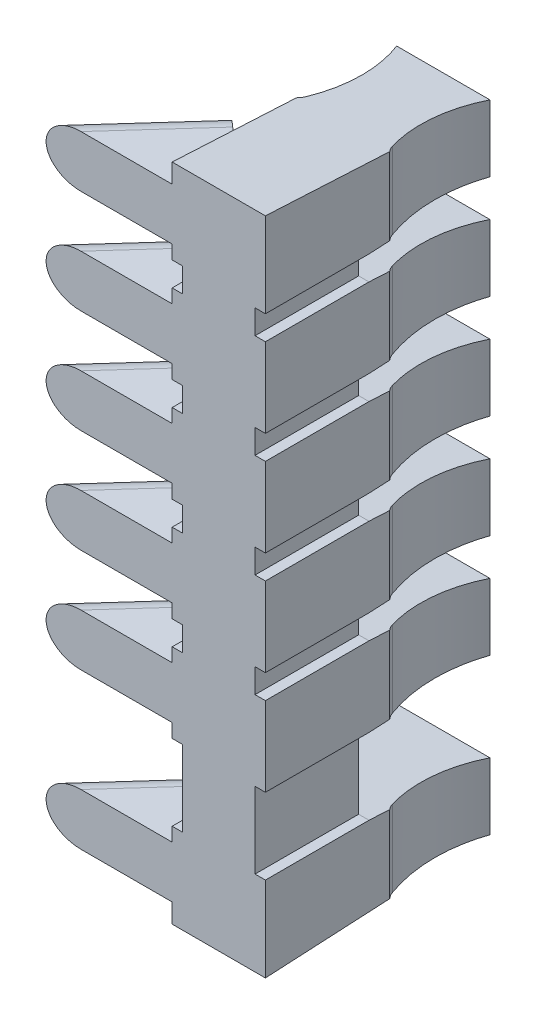
SolidWorks part; units mm, degrees
ref_plane "Front Plane" through (0, 0, 0) normal (0, 0, 1) x (1, 0, 0)
ref_plane "Top Plane" through (0, 0, 0) normal (0, 1, 0) x (1, 0, 0)
ref_plane "Right Plane" through (0, 0, 0) normal (1, 0, 0) x (0, 0, -1)
sketch "Sketch1" plane through (0, 0, 0) normal (0, 0, 1) x (1, 0, 0)
  line L0 (-7.5, 0) -> (0, 0) construction
  line L1 (-7.5, 15) -> (7.5, 15)
  line L2 (-7.5, 15) -> (-7.5, -15)
  line L3 (-7.5, -15) -> (7.5, -15)
  line L4 (7.5, 15) -> (7.5, -15)
  line L5 (0, 0) -> (0, 15) construction
  dimension "D1" = 15
  dimension "D2" = 30
sketch "Sketch2" plane through (0, 0, 0) normal (1, 0, 0) x (0, 0, -1)
  line L1 (0, 15) -> (7, 15)
  line L2 (0, 15) -> (0, -15)
  line L3 (0, -15) -> (7, -15)
  line L4 (7, 15) -> (7, -15)
  dimension "D1" = 7
extrude "Boss-Extrude1" add sketch "Sketch1" against normal up to vertex (7 mm away) up to point (0, 15, -7)
ref_plane "Plane1" through (1.35, 0, 0) normal (1, 0, 0) x (0, 0, -1)
sketch "Sketch7" plane through (1.35, 0, 0) normal (1, 0, 0) x (0, 0, -1)
  line L0 (3, 4.1005) -> (0, 4.1005) construction
  line L1 (0, 4.1005) -> (0, 6.3995) construction
  line L2 (3, 6.3995) -> (0, 6.3995) construction
  line L3 (3, 6.3995) -> (6.5, 6.2161) construction
  line L4 (6.5, 6.2161) -> (6.5, 4.2839) construction
  line L5 (6.5, 4.2839) -> (3, 4.1005) construction
  line L6 (3, 1.1005) -> (0, 1.1005) construction
  line L7 (0, 1.1005) -> (0, 3.3995) construction
  line L8 (3, 3.3995) -> (0, 3.3995) construction
  line L9 (6.5, 3.2161) -> (3, 3.3995) construction
  line L10 (6.5, 1.2839) -> (6.5, 3.2161) construction
  line L11 (3, 1.1005) -> (6.5, 1.2839) construction
  line L12 (3, -1.8995) -> (0, -1.8995) construction
  line L13 (0, -1.8995) -> (0, 0.3995) construction
  line L14 (3, 0.3995) -> (0, 0.3995) construction
  line L15 (3, 0.3995) -> (6.5, 0.2161) construction
  line L16 (6.5, 0.2161) -> (6.5, -1.7161) construction
  line L17 (6.5, -1.7161) -> (3, -1.8995) construction
  line L19 (3, -4.8995) -> (0, -4.8995) construction
  line L20 (0, -4.8995) -> (0, -2.6005) construction
  line L21 (3, -2.6005) -> (0, -2.6005) construction
  line L22 (6.5, -2.7839) -> (3, -2.6005) construction
  line L23 (6.5, -4.7161) -> (6.5, -2.7839) construction
  line L24 (3, -4.8995) -> (6.5, -4.7161) construction
  line L25 (3, -7.1005) -> (0, -7.1005) construction
  line L26 (0, -9.5567) -> (0, -7.1005) construction
  line L27 (6.5, -9.2161) -> (0, -9.5567) construction
  line L28 (6.5, -7.2839) -> (6.5, -9.2161) construction
  line L29 (3, -7.1005) -> (6.5, -7.2839) construction
  line L30 (3, 7.1005) -> (0, 7.1005) construction
  line L31 (0, 7.1005) -> (0, 9.5567) construction
  line L32 (6.5, 9.2161) -> (0, 9.5567) construction
  line L33 (6.5, 7.2839) -> (6.5, 9.2161) construction
  line L34 (3, 7.1005) -> (6.5, 7.2839) construction
  line L35 (3, 4.1005) -> (0, 4.1005)
  line L36 (0, 4.1005) -> (0, 6.3995)
  line L37 (3, 6.3995) -> (0, 6.3995)
  line L38 (3, 6.3995) -> (6.5, 6.2161)
  line L39 (6.5, 6.2161) -> (6.5, 4.2839)
  line L40 (6.5, 4.2839) -> (3, 4.1005)
  line L41 (3, 1.1005) -> (0, 1.1005)
  line L42 (0, 1.1005) -> (0, 3.3995)
  line L43 (3, 3.3995) -> (0, 3.3995)
  line L44 (6.5, 3.2161) -> (3, 3.3995)
  line L45 (6.5, 1.2839) -> (6.5, 3.2161)
  line L46 (3, 1.1005) -> (6.5, 1.2839)
  line L47 (3, -1.8995) -> (0, -1.8995)
  line L48 (0, -1.8995) -> (0, 0.3995)
  line L49 (3, 0.3995) -> (0, 0.3995)
  line L50 (3, 0.3995) -> (6.5, 0.2161)
  line L51 (6.5, 0.2161) -> (6.5, -1.7161)
  line L52 (6.5, -1.7161) -> (3, -1.8995)
  line L54 (3, -4.8995) -> (0, -4.8995)
  line L55 (0, -4.8995) -> (0, -2.6005)
  line L56 (3, -2.6005) -> (0, -2.6005)
  line L57 (6.5, -2.7839) -> (3, -2.6005)
  line L58 (6.5, -4.7161) -> (6.5, -2.7839)
  line L59 (3, -4.8995) -> (6.5, -4.7161)
  line L60 (3, -7.1005) -> (0, -7.1005)
  line L61 (0, -9.5567) -> (0, -7.1005)
  line L62 (6.5, -9.2161) -> (0, -9.5567)
  line L63 (6.5, -7.2839) -> (6.5, -9.2161)
  line L64 (3, -7.1005) -> (6.5, -7.2839)
  line L65 (3, 7.1005) -> (0, 7.1005)
  line L66 (0, 7.1005) -> (0, 9.5567)
  line L67 (6.5, 9.2161) -> (0, 9.5567)
  line L68 (6.5, 7.2839) -> (6.5, 9.2161)
  line L69 (3, 7.1005) -> (6.5, 7.2839)
sketch "Sketch8" plane through (1.35, 0, 0) normal (1, 0, 0) x (0, 0, -1)
  line L0 (6.5, -4.7161) -> (6.5, -2.7839) construction
  line L1 (6.5, -2.7839) -> (3, -2.6005) construction
  line L2 (3, -2.6005) -> (3, -1.8995) construction
  line L3 (6.5, -1.7161) -> (3, -1.8995) construction
  line L4 (6.5, 0.2161) -> (6.5, -1.7161) construction
  line L5 (3, 0.3995) -> (6.5, 0.2161) construction
  line L6 (3, 0.3995) -> (3, 1.1005) construction
  line L7 (3, 1.1005) -> (6.5, 1.2839) construction
  line L8 (6.5, 1.2839) -> (6.5, 3.2161) construction
  line L9 (6.5, 3.2161) -> (3, 3.3995) construction
  line L10 (3, 3.3995) -> (3, 4.1005) construction
  line L11 (6.5, 4.2839) -> (3, 4.1005) construction
  line L12 (6.5, 6.2161) -> (6.5, 4.2839) construction
  line L13 (3, 6.3995) -> (6.5, 6.2161) construction
  line L14 (3, 6.3995) -> (3, 7.1005) construction
  line L15 (3, 7.1005) -> (6.5, 7.2839) construction
  line L16 (6.5, 7.2839) -> (6.5, 9.2161) construction
  line L17 (6.5, 9.2161) -> (0, 9.5567) construction
  line L18 (0, 9.5567) -> (0, -9.5567) construction
  line L19 (6.5, -9.2161) -> (0, -9.5567) construction
  line L20 (6.5, -7.2839) -> (6.5, -9.2161) construction
  line L21 (3, -7.1005) -> (6.5, -7.2839) construction
  line L22 (3, -7.1005) -> (3, -4.8995) construction
  line L23 (3, -4.8995) -> (6.5, -4.7161) construction
  line L24 (6.5, -4.7161) -> (6.5, -2.7839)
  line L25 (6.5, -2.7839) -> (3, -2.6005)
  line L26 (3, -2.6005) -> (3, -1.8995)
  line L27 (6.5, -1.7161) -> (3, -1.8995)
  line L28 (6.5, 0.2161) -> (6.5, -1.7161)
  line L29 (3, 0.3995) -> (6.5, 0.2161)
  line L30 (3, 0.3995) -> (3, 1.1005)
  line L31 (3, 1.1005) -> (6.5, 1.2839)
  line L32 (6.5, 1.2839) -> (6.5, 3.2161)
  line L33 (6.5, 3.2161) -> (3, 3.3995)
  line L34 (3, 3.3995) -> (3, 4.1005)
  line L35 (6.5, 4.2839) -> (3, 4.1005)
  line L36 (6.5, 6.2161) -> (6.5, 4.2839)
  line L37 (3, 6.3995) -> (6.5, 6.2161)
  line L38 (3, 6.3995) -> (3, 7.1005)
  line L39 (3, 7.1005) -> (6.5, 7.2839)
  line L40 (6.5, 7.2839) -> (6.5, 9.2161)
  line L41 (6.5, 9.2161) -> (0, 9.5567)
  line L42 (0, 9.5567) -> (0, -9.5567)
  line L43 (6.5, -9.2161) -> (0, -9.5567)
  line L44 (6.5, -7.2839) -> (6.5, -9.2161)
  line L45 (3, -7.1005) -> (6.5, -7.2839)
  line L46 (3, -7.1005) -> (3, -4.8995)
  line L47 (3, -4.8995) -> (6.5, -4.7161)
sketch "Sketch9" plane through (0, 0, 0) normal (0, 0, 1) x (1, 0, 0)
  line L0 (-1.35, 9.5567) -> (-1.35, -9.5567) construction
  line L1 (1.35, -9.5567) -> (-1.35, -9.5567) construction
  line L2 (1.35, 9.5567) -> (1.35, -9.5567) construction
  line L3 (1.35, 9.5567) -> (-1.35, 9.5567) construction
  line L4 (-1.35, 9.5567) -> (-1.35, -9.5567) construction
  line L5 (1.35, -9.5567) -> (-1.35, -9.5567) construction
  line L6 (1.35, 9.5567) -> (1.35, -9.5567) construction
  line L7 (1.35, 9.5567) -> (-1.35, 9.5567) construction
  line L8 (0, -9.5567) -> (0, 9.5567) construction
  line L9 (-1.35, 0) -> (1.35, 0) construction
  line L10 (0.75, -9.1562) -> (-0.75, -9.1562) construction
  line L11 (-0.75, 9.1562) -> (-0.75, -9.1562) construction
  line L12 (0.75, 9.1562) -> (-0.75, 9.1562) construction
  line L13 (0.75, -9.1562) -> (-0.75, -9.1562)
  line L14 (-0.75, 9.1562) -> (-0.75, -9.1562)
  line L15 (0.75, 9.1562) -> (-0.75, 9.1562)
  line L16 (0.75, -9.1562) -> (0.75, 9.1562)
  line L17 (1.05, -9.5567) -> (1.05, 9.5567) construction
  line L18 (-1.05, -9.5567) -> (-1.05, 9.5567) construction
  line L19 (1.05, -9.5567) -> (1.05, 9.5567) construction
  line L20 (-1.05, -9.5567) -> (-1.05, 9.5567) construction
ref_plane "Plane2" through (0, -9.5567, 0) normal (0, 1, 0) x (1, 0, 0)
sketch "Sketch10" plane through (0, -9.5567, 0) normal (0, 1, 0) x (1, 0, 0)
  line L0 (1.35, 3.5995) -> (1.35, 6.5)
  line L1 (-1.35, 3.5995) -> (-1.35, 6.5)
  arc A0 (-1.2465, 3.7776) -> (-1.35, 6.5) centre (-4.95, 5) ccw construction
  arc A1 (-1.35, 3.5995) -> (-1.2465, 3.7776) centre (-1.7213, 3.9344) ccw construction
  arc A2 (1.2465, 3.7776) -> (1.35, 3.5995) centre (1.7213, 3.9344) ccw construction
  arc A3 (1.35, 6.5) -> (1.2465, 3.7776) centre (4.95, 5) ccw construction
  arc A4 (-1.2465, 3.7776) -> (-1.35, 6.5) centre (-4.95, 5) ccw
  arc A5 (-1.35, 3.5995) -> (-1.2465, 3.7776) centre (-1.7213, 3.9344) ccw
  arc A6 (1.2465, 3.7776) -> (1.35, 3.5995) centre (1.7213, 3.9344) ccw
  arc A7 (1.35, 6.5) -> (1.2465, 3.7776) centre (4.95, 5) ccw
ref_plane "Plane3" through (2.213, 9.1562, -4.3777) normal (0.6697, 0, 0.7426) x (0, -1, 0)
sketch "Sketch11" plane through (2.213, 9.1562, -4.3777) normal (0.6697, 0, 0.7426) x (0, -1, 0)
  line L0 (0.4562, -2.362) -> (0.4562, -1.612) construction
  line L1 (1.3562, -1.612) -> (1.3562, -2.362) construction
  line L2 (1.3562, -2.362) -> (0.4562, -2.362) construction
  line L3 (3.4562, -1.612) -> (3.4562, -2.362) construction
  line L4 (3.4562, -2.362) -> (4.3562, -2.362) construction
  line L5 (4.3562, -2.362) -> (4.3562, -1.612) construction
  line L6 (7.3562, -1.612) -> (7.3562, -2.362) construction
  line L7 (7.3562, -2.362) -> (6.4562, -2.362) construction
  line L8 (6.4562, -2.362) -> (6.4562, -1.612) construction
  line L9 (9.4562, -1.612) -> (9.4562, -2.362) construction
  line L10 (9.4562, -2.362) -> (10.3562, -2.362) construction
  line L11 (10.3562, -2.362) -> (10.3562, -1.612) construction
  line L12 (13.3562, -1.612) -> (13.3562, -2.362) construction
  line L13 (13.3562, -2.362) -> (12.4562, -2.362) construction
  line L14 (12.4562, -2.362) -> (12.4562, -1.612) construction
  line L15 (16.9562, -1.612) -> (16.9562, -2.362) construction
  line L16 (16.9562, -2.362) -> (17.8562, -2.362) construction
  line L17 (17.8562, -2.362) -> (17.8562, -1.612) construction
  line L18 (0.4562, -2.362) -> (0.4562, -1.612)
  line L19 (1.3562, -1.612) -> (1.3562, -2.362)
  line L20 (1.3562, -2.362) -> (0.4562, -2.362)
  line L21 (3.4562, -1.612) -> (3.4562, -2.362)
  line L22 (3.4562, -2.362) -> (4.3562, -2.362)
  line L23 (4.3562, -2.362) -> (4.3562, -1.612)
  line L24 (7.3562, -1.612) -> (7.3562, -2.362)
  line L25 (7.3562, -2.362) -> (6.4562, -2.362)
  line L26 (6.4562, -2.362) -> (6.4562, -1.612)
  line L27 (9.4562, -1.612) -> (9.4562, -2.362)
  line L28 (9.4562, -2.362) -> (10.3562, -2.362)
  line L29 (10.3562, -2.362) -> (10.3562, -1.612)
  line L30 (13.3562, -1.612) -> (13.3562, -2.362)
  line L31 (13.3562, -2.362) -> (12.4562, -2.362)
  line L32 (12.4562, -2.362) -> (12.4562, -1.612)
  line L33 (16.9562, -1.612) -> (16.9562, -2.362)
  line L34 (16.9562, -2.362) -> (17.8562, -2.362)
  line L35 (17.8562, -2.362) -> (17.8562, -1.612)
  arc A0 (1.3562, -1.612) -> (0.4562, -1.612) centre (0.9062, -1.612) ccw construction
  arc A1 (4.3562, -1.612) -> (3.4562, -1.612) centre (3.9062, -1.612) ccw construction
  arc A2 (7.3562, -1.612) -> (6.4562, -1.612) centre (6.9062, -1.612) ccw construction
  arc A3 (10.3562, -1.612) -> (9.4562, -1.612) centre (9.9062, -1.612) ccw construction
  arc A4 (13.3562, -1.612) -> (12.4562, -1.612) centre (12.9062, -1.612) ccw construction
  arc A5 (17.8562, -1.612) -> (16.9562, -1.612) centre (17.4062, -1.612) ccw construction
  arc A6 (1.3562, -1.612) -> (0.4562, -1.612) centre (0.9062, -1.612) ccw
  arc A7 (4.3562, -1.612) -> (3.4562, -1.612) centre (3.9062, -1.612) ccw
  arc A8 (7.3562, -1.612) -> (6.4562, -1.612) centre (6.9062, -1.612) ccw
  arc A9 (10.3562, -1.612) -> (9.4562, -1.612) centre (9.9062, -1.612) ccw
  arc A10 (13.3562, -1.612) -> (12.4562, -1.612) centre (12.9062, -1.612) ccw
  arc A11 (17.8562, -1.612) -> (16.9562, -1.612) centre (17.4062, -1.612) ccw
ref_plane "Plane4" through (3.1041, 9.1562, -3.3895) normal (0.6697, 0, 0.7426) x (0, -1, 0)
sketch "Sketch12" plane through (3.1041, 9.1562, -3.3895) normal (0.6697, 0, 0.7426) x (0, -1, 0)
  line L0 (0.1562, -1.612) -> (0.1562, -5.0612) construction
  line L1 (0.1562, -5.0612) -> (1.6562, -5.0612) construction
  line L2 (1.6562, -1.612) -> (1.6562, -5.0612) construction
  line L3 (3.1562, -1.612) -> (3.1562, -5.0612) construction
  line L4 (4.6562, -5.0612) -> (3.1562, -5.0612) construction
  line L5 (4.6562, -1.612) -> (4.6562, -5.0612) construction
  line L6 (6.1562, -1.612) -> (6.1562, -5.0612) construction
  line L7 (6.1562, -5.0612) -> (7.6562, -5.0612) construction
  line L8 (7.6562, -1.612) -> (7.6562, -5.0612) construction
  line L9 (9.1562, -1.612) -> (9.1562, -5.0612) construction
  line L10 (10.6562, -5.0612) -> (9.1562, -5.0612) construction
  line L11 (10.6562, -1.612) -> (10.6562, -5.0612) construction
  line L12 (12.1562, -1.612) -> (12.1562, -5.0612) construction
  line L13 (12.1562, -5.0612) -> (13.6562, -5.0612) construction
  line L14 (13.6562, -1.612) -> (13.6562, -5.0612) construction
  line L15 (16.6562, -1.612) -> (16.6562, -5.0612) construction
  line L16 (18.1562, -5.0612) -> (16.6562, -5.0612) construction
  line L17 (18.1562, -1.612) -> (18.1562, -5.0612) construction
  line L18 (0.1562, -1.612) -> (0.1562, -5.0612)
  line L19 (0.1562, -5.0612) -> (1.6562, -5.0612)
  line L20 (1.6562, -1.612) -> (1.6562, -5.0612)
  line L21 (3.1562, -1.612) -> (3.1562, -5.0612)
  line L22 (4.6562, -5.0612) -> (3.1562, -5.0612)
  line L23 (4.6562, -1.612) -> (4.6562, -5.0612)
  line L24 (6.1562, -1.612) -> (6.1562, -5.0612)
  line L25 (6.1562, -5.0612) -> (7.6562, -5.0612)
  line L26 (7.6562, -1.612) -> (7.6562, -5.0612)
  line L27 (9.1562, -1.612) -> (9.1562, -5.0612)
  line L28 (10.6562, -5.0612) -> (9.1562, -5.0612)
  line L29 (10.6562, -1.612) -> (10.6562, -5.0612)
  line L30 (12.1562, -1.612) -> (12.1562, -5.0612)
  line L31 (12.1562, -5.0612) -> (13.6562, -5.0612)
  line L32 (13.6562, -1.612) -> (13.6562, -5.0612)
  line L33 (16.6562, -1.612) -> (16.6562, -5.0612)
  line L34 (18.1562, -5.0612) -> (16.6562, -5.0612)
  line L35 (18.1562, -1.612) -> (18.1562, -5.0612)
  arc A0 (1.6562, -1.612) -> (0.1562, -1.612) centre (0.9062, -1.612) ccw construction
  arc A1 (4.6562, -1.612) -> (3.1562, -1.612) centre (3.9062, -1.612) ccw construction
  arc A2 (7.6562, -1.612) -> (6.1562, -1.612) centre (6.9062, -1.612) ccw construction
  arc A3 (10.6562, -1.612) -> (9.1562, -1.612) centre (9.9062, -1.612) ccw construction
  arc A4 (13.6562, -1.612) -> (12.1562, -1.612) centre (12.9062, -1.612) ccw construction
  arc A5 (18.1562, -1.612) -> (16.6562, -1.612) centre (17.4062, -1.612) ccw construction
  arc A6 (1.6562, -1.612) -> (0.1562, -1.612) centre (0.9062, -1.612) ccw
  arc A7 (4.6562, -1.612) -> (3.1562, -1.612) centre (3.9062, -1.612) ccw
  arc A8 (7.6562, -1.612) -> (6.1562, -1.612) centre (6.9062, -1.612) ccw
  arc A9 (10.6562, -1.612) -> (9.1562, -1.612) centre (9.9062, -1.612) ccw
  arc A10 (13.6562, -1.612) -> (12.1562, -1.612) centre (12.9062, -1.612) ccw
  arc A11 (18.1562, -1.612) -> (16.6562, -1.612) centre (17.4062, -1.612) ccw
extrude "Cut-Extrude1" cut sketch "Sketch8" against normal up to vertex (2.4 mm away) from vertex at -0.3 starting at point (1.05, -9.5567, 0)
extrude "Cut-Extrude4" cut sketch "Sketch7" against normal up to vertex (2.7 mm away) up to point (-1.35, -9.5567, 0)
extrude "Boss-Extrude2" add sketch "Sketch10" along normal up to vertex (24.5567 mm away)
extrude "Cut-Extrude2" cut sketch "Sketch12" along normal through all
extrude "Cut-Extrude3" cut sketch "Sketch11" along normal through all
mirror "Mirror1" about plane through (0, 0, 0) normal (1, 0, 0) of "Cut-Extrude2", "Cut-Extrude3"
sketch "Sketch13" plane through (0, 0, 0) normal (0, 0, 1) x (1, 0, 0)
  line L0 (0, 0) -> (-5, 0) construction
  line L1 (-5, -10) -> (5, -10)
  line L2 (-5, -10) -> (-5, 10)
  line L3 (-5, 10) -> (5, 10)
  line L4 (5, -10) -> (5, 10)
  line L5 (0, 0) -> (5, 0) construction
  line L6 (0, 0) -> (0, 10) construction
  line L7 (0, 0) -> (0, -10) construction
  dimension "D1" = 20
  dimension "D2" = 10
extrude "Boss-Extrude3" add sketch "Sketch13" against normal blind 7 separate body
combine bodies "Combine1" operation type subtract main body 114 bodies to subtract 112
sketch "Sketch14" plane through (0, 0, 0) normal (0, 0, 1) x (1, 0, 0)
  line L1 (1.35, -9.5567) -> (5, -9.5567)
  line L2 (1.35, -9.5567) -> (1.35, 9.5567)
  line L3 (1.35, 9.5567) -> (5, 9.5567)
  line L4 (5, -9.5567) -> (5, 9.5567)
  ellipse E0 centre (3.9901, 2.25) end of major axis (5, 2.25) minor radius 0.75 (3.9901, 1.5) -> (3.9901, 3) ccw construction
extrude "Cut-Extrude5" cut sketch "Sketch14" against normal through all
